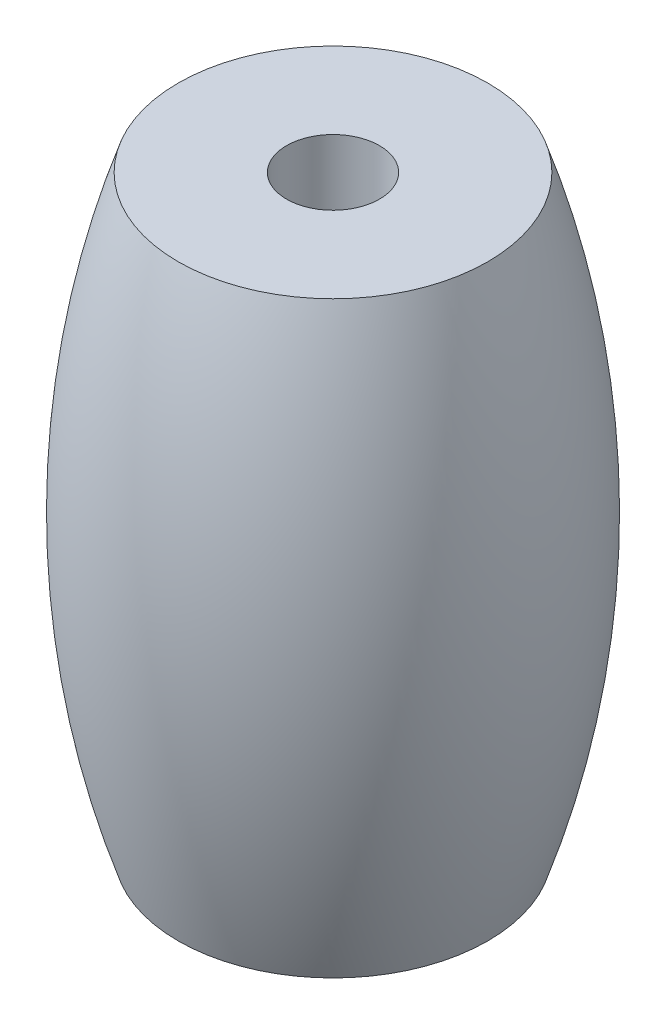
SolidWorks part; units mm, degrees
ref_plane "前视基准面" through (0, 0, 0) normal (0, 0, 1) x (1, 0, 0)
ref_plane "上视基准面" through (0, 0, 0) normal (0, 1, 0) x (1, 0, 0)
ref_plane "右视基准面" through (0, 0, 0) normal (1, 0, 0) x (0, 0, -1)
sketch "草图1" plane through (0, 0, 0) normal (0, 0, 1) x (1, 0, 0)
  line L0 (-1.5, 16.5644) -> (-1.5, -2.4356)
  line L1 (-1.5, -2.4356) -> (-5, -2.4356)
  line L2 (-1.5, 16.5644) -> (-5, 16.5644)
  line L3 (0, 0) -> (0, 19.2124) construction
  arc A1 (-5, 16.5644) -> (-5, -2.4356) centre (23.4561, 7.0644) ccw
  dimension "D1" = 1.5
  dimension "D2" = 19
  dimension "D3" = 3.5
  dimension "D4" = 3.5
revolve "旋转1" add sketch "草图1" angle 360 about L3
